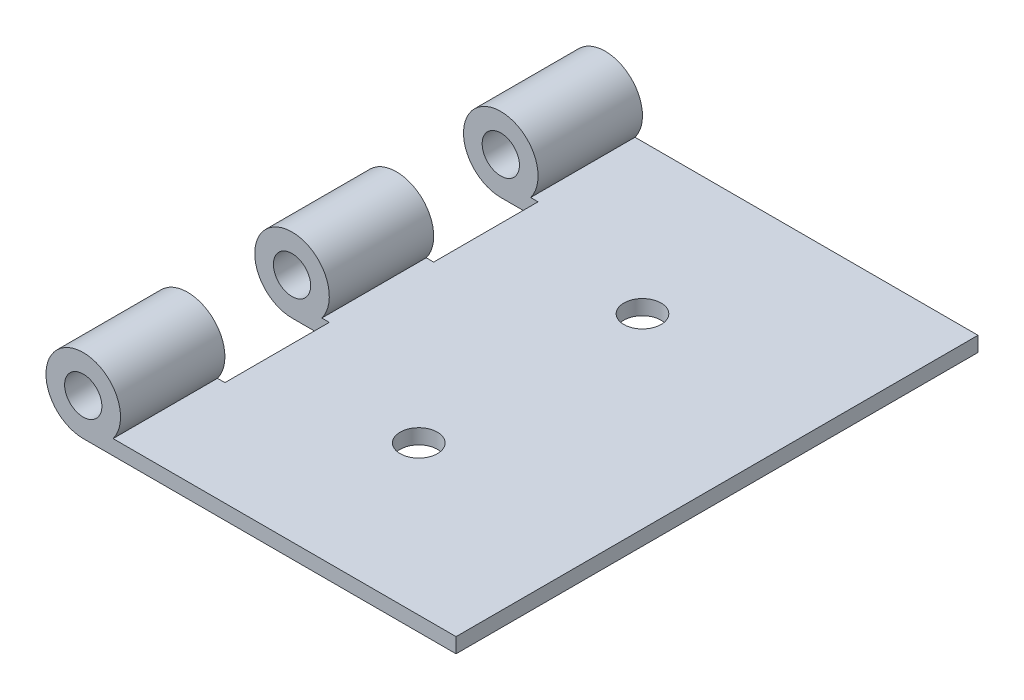
SolidWorks part; units mm, degrees
ref_plane "Front Plane" through (0, 0, 0) normal (0, 0, 1) x (1, 0, 0)
ref_plane "Top Plane" through (0, 0, 0) normal (0, 1, 0) x (1, 0, 0)
ref_plane "Right Plane" through (0, 0, 0) normal (1, 0, 0) x (0, 0, -1)
sketch "Sketch1" plane through (0, 0, 0) normal (0, 1, 0) x (1, 0, 0)
  line L1 (-25, 35) -> (25, 35)
  line L2 (-25, 35) -> (-25, -35)
  line L3 (-25, -35) -> (25, -35)
  line L4 (25, 35) -> (25, -35)
  line L5 (-25, 35) -> (25, -35) construction
  line L6 (-25, -35) -> (25, 35) construction
  point P0 (0, 0)
  dimension "D1" = 50
  dimension "D2" = 70
extrude "Boss-Extrude1" add sketch "Sketch1" along normal blind 2
sketch "Sketch2" plane through (0, 0, 35) normal (0, 0, 1) x (1, 0, 0)
  circle A0 centre (-25, 5) radius 2.5
  circle A1 centre (-25, 5) radius 5
  point P3 (0, 0)
  dimension "D1" = 10
  dimension "D2" = 5
extrude "Boss-Extrude2" add sketch "Sketch2" against normal up to surface (70 mm away) up to face at (0, 1, -35)
sketch "Sketch3" plane through (0, 2, 0) normal (0, 1, 0) x (1, 0, 0)
  line L0 (25, -35) -> (25, 35) construction
  line L1 (-21, -35) -> (25, -35) construction
  line L2 (25, 35) -> (-21, 35) construction
  circle A0 centre (0, 15) radius 2.5
  circle A1 centre (0, -15) radius 2.5
  dimension "D1" = 5
  dimension "D2" = 5
  dimension "D4" = 25
  dimension "D5" = 20
  dimension "D6" = 20
  dimension "D3" = 25
extrude "Cut-Extrude1" cut sketch "Sketch3" against normal through all
sketch "Sketch4" plane through (0, 2, 0) normal (0, 1, 0) x (1, 0, 0)
  line L0 (-30, 35) -> (-30, -35) construction
  line L1 (-30, -7) -> (-20, -7)
  line L2 (-30, -7) -> (-30, -21)
  line L3 (-30, -21) -> (-20, -21)
  line L4 (-20, -7) -> (-20, -21)
  line L5 (-20, -35) -> (-20, 35) construction
  line L7 (-30, 21) -> (-20, 21)
  line L8 (-30, 21) -> (-30, 7)
  line L9 (-30, 7) -> (-20, 7)
  line L10 (-20, 21) -> (-20, 7)
  line L11 (-30, -35) -> (-20, -35) construction
  line L12 (25, -35) -> (25, 35) construction
  dimension "D1" = 14
  dimension "D2" = 14
  dimension "D3" = 10
  dimension "D4" = 14
  dimension "D5" = 14
extrude "Cut-Extrude2" cut sketch "Sketch4" against normal through all both and the other way through all
